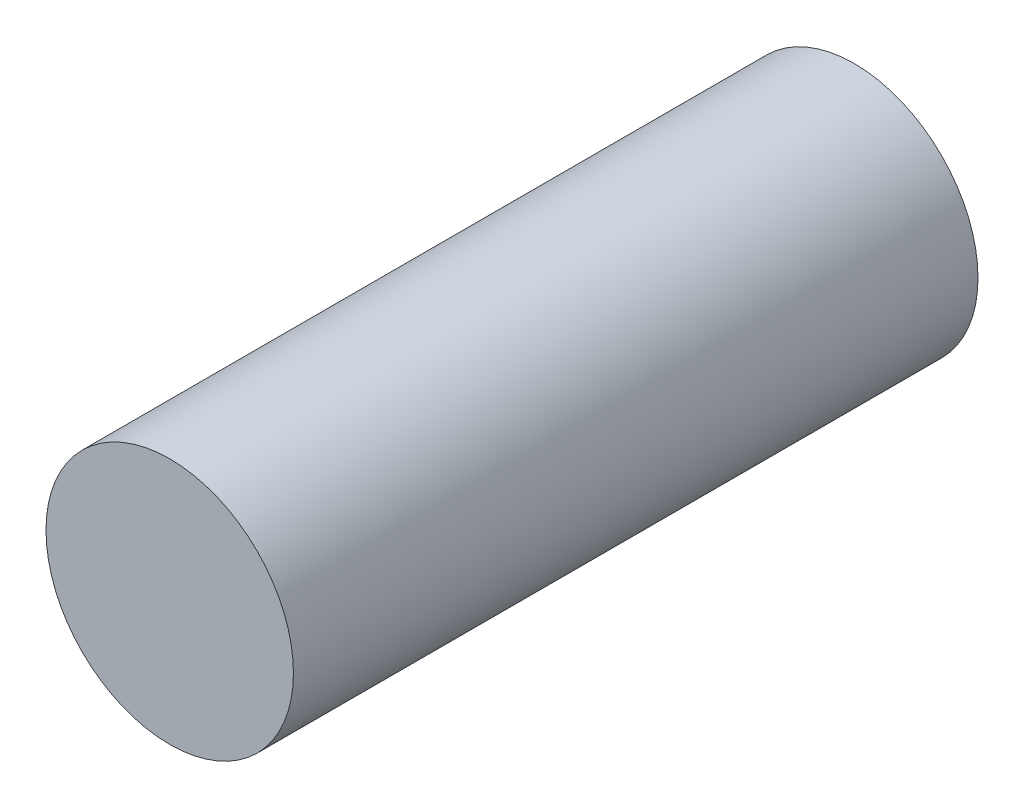
SolidWorks part; units mm, degrees
ref_plane "Alzado" through (0, 0, 0) normal (0, 0, 1) x (1, 0, 0)
ref_plane "Planta" through (0, 0, 0) normal (0, 1, 0) x (1, 0, 0)
ref_plane "Vista lateral" through (0, 0, 0) normal (1, 0, 0) x (0, 0, -1)
sketch "Croquis1" plane through (0, 0, 0) normal (0, 0, 1) x (1, 0, 0)
  circle A0 centre (0, 0) radius 7.5
  point P4 (0, 0)
  dimension "D1" = 15
extrude "Saliente-Extruir1" add sketch "Croquis1" along normal blind 41.5
